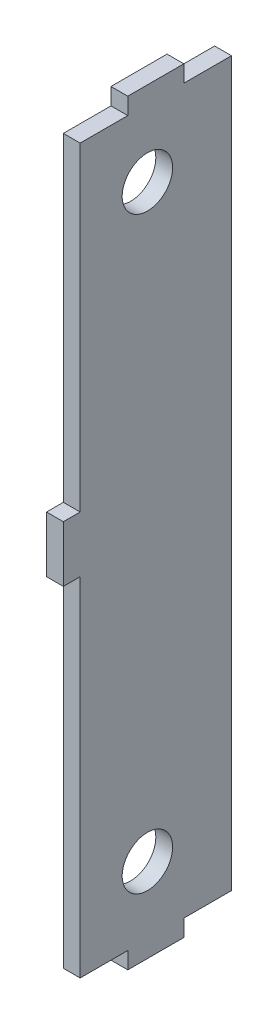
SolidWorks part; units mm, degrees
ref_plane "Front Plane" through (0, 0, 0) normal (0, 0, 1) x (1, 0, 0)
ref_plane "Top Plane" through (0, 0, 0) normal (0, 1, 0) x (1, 0, 0)
ref_plane "Right Plane" through (0, 0, 0) normal (1, 0, 0) x (0, 0, -1)
sketch "Sketch1" plane through (0, 0, 0) normal (1, 0, 0) x (0, 0, -1)
  line L0 (0, 55) -> (0, -55) construction
  line L1 (0, 64.5) -> (-8.5, 64.5)
  line L2 (0, 64.5) -> (0, -64.5)
  line L3 (0, -64.5) -> (-8.5, -64.5)
  line L4 (-27, 64.5) -> (-27, 7.5)
  line L5 (-27, -2.5) -> (-27, -64.5)
  line L7 (-27, 7.5) -> (-30, 7.5)
  line L9 (-27, -2.5) -> (-30, -2.5)
  line L10 (-30, 7.5) -> (-30, -2.5)
  line L12 (-18.5, 64.5) -> (-18.5, 67.5)
  line L13 (-18.5, 67.5) -> (-8.5, 67.5)
  line L14 (-8.5, 64.5) -> (-8.5, 67.5)
  line L16 (-18.5, -64.5) -> (-18.5, -67.5)
  line L17 (-18.5, -67.5) -> (-8.5, -67.5)
  line L18 (-8.5, -64.5) -> (-8.5, -67.5)
  line L19 (-18.5, 64.5) -> (-27, 64.5)
  line L20 (-18.5, -64.5) -> (-27, -64.5)
  line L21 (-13.5, -67.5) -> (-13.5, 67.5) construction
  dimension "D1" = 27
  dimension "D2" = 129
  dimension "D3" = 10
  dimension "D4" = 3
  dimension "D5" = 57
extrude "Boss-Extrude1" add sketch "Sketch1" along normal blind 3
sketch "Sketch2" plane through (3, 0, 0) normal (1, 0, 0) x (0, 0, -1)
  line L0 (-8.5, 67.5) -> (-18.5, 67.5) construction
  line L1 (0, 1.65) -> (0, -1.65) construction
  circle A0 centre (-15, 52.5) radius 4.5
  circle A1 centre (-15, -52.5) radius 4.5
  dimension "D1" = 15
  dimension "D3" = 9
  dimension "D4" = 105
  dimension "D2" = 15
extrude "Cut-Extrude1" cut sketch "Sketch2" against normal through all
